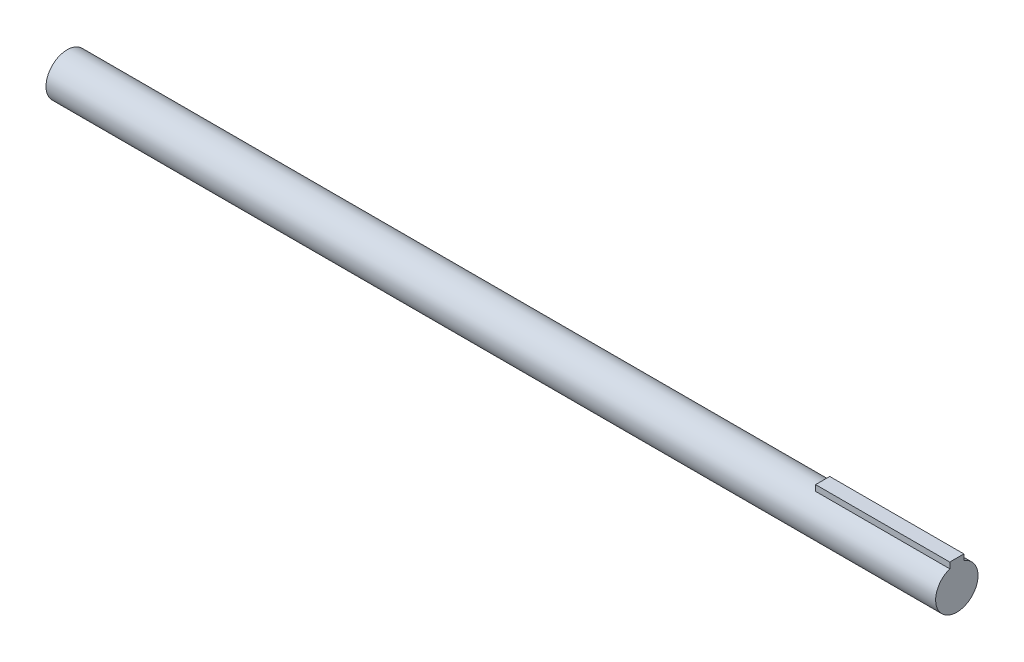
SolidWorks part; units mm, degrees
material "1023 Carbon Steel Sheet (SS)"
ref_plane "Front Plane" through (0, 0, 0) normal (0, 0, 1) x (1, 0, 0)
ref_plane "Top Plane" through (0, 0, 0) normal (0, 1, 0) x (1, 0, 0)
ref_plane "Right Plane" through (0, 0, 0) normal (1, 0, 0) x (0, 0, -1)
sketch "Sketch1" plane through (0, 0, 0) normal (1, 0, 0) x (0, 0, -1)
  circle A0 centre (0, 0) radius 15
extrude "Boss-Extrude1" add sketch "Sketch1" along normal blind 590
sketch "Sketch2" plane through (590, 0, 0) normal (1, 0, 0) x (0, 0, -1)
  line L0 (0, 15) -> (5, 15) construction
  line L1 (0, 15) -> (-5, 15) construction
  line L2 (5, 14.1421) -> (5, 18.3021)
  line L3 (5, 18.3021) -> (-5, 18.3021)
  line L4 (-5, 18.3021) -> (-5, 14.1421)
  circle A0 centre (0, 0) radius 15 construction
  arc A1 (5, 14.1421) -> (-5, 14.1421) centre (0, 0) ccw
extrude "Boss-Extrude3" add sketch "Sketch2" against normal blind 55
sketch "Sketch3" plane through (590, 0, 0) normal (1, 0, 0) x (0, 0, -1)
  line L0 (-5, 18.3021) -> (-5, 14.1421) construction
  line L1 (-5, 18.3021) -> (-5, 14.1421)
  line L2 (5, 18.3021) -> (-5, 18.3021) construction
  line L3 (5, 18.3021) -> (-5, 18.3021)
  line L4 (5, 14.1421) -> (5, 18.3021) construction
  line L5 (5, 14.1421) -> (5, 18.3021)
  arc A0 (-5, 14.1421) -> (5, 14.1421) centre (0, 0) ccw
extrude "Boss-Extrude4" add sketch "Sketch3" along normal blind 40
